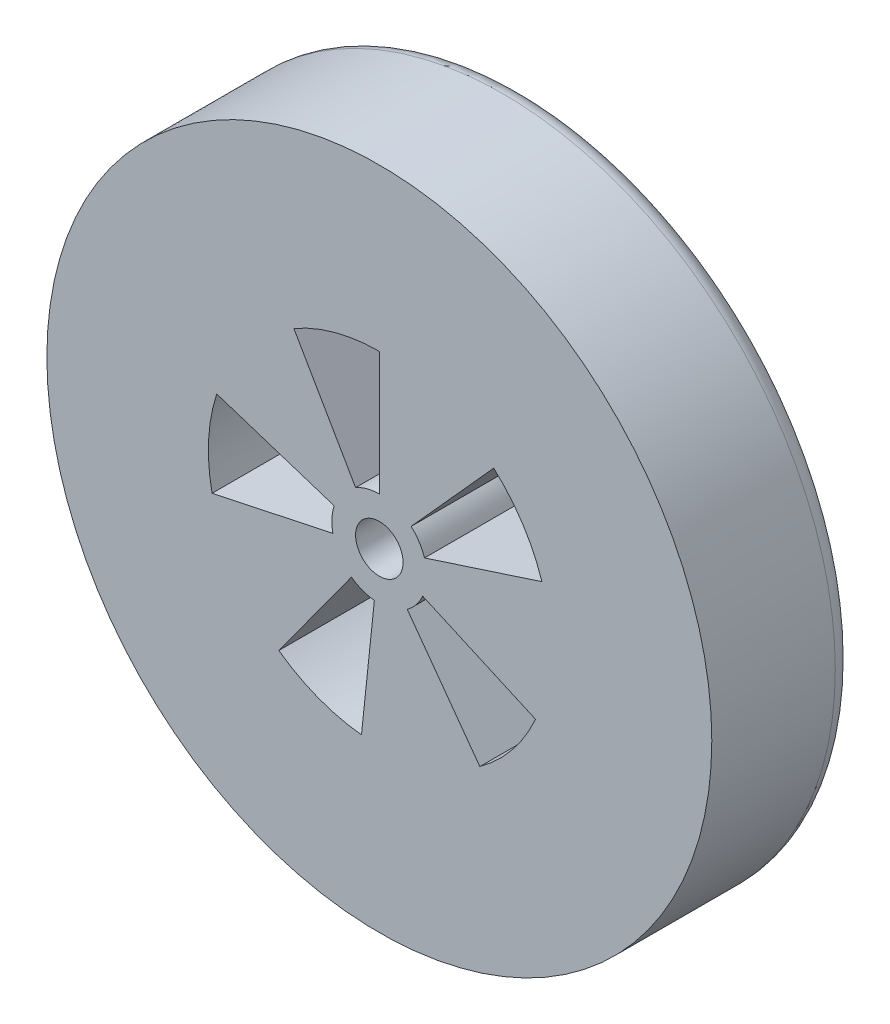
SolidWorks part; units mm, degrees
ref_plane "Front Plane" through (0, 0, 0) normal (0, 0, 1) x (1, 0, 0)
ref_plane "Top Plane" through (0, 0, 0) normal (0, 1, 0) x (1, 0, 0)
ref_plane "Right Plane" through (0, 0, 0) normal (1, 0, 0) x (0, 0, -1)
sketch "Sketch1" plane through (0, 0, 0) normal (0, 0, 1) x (1, 0, 0)
  circle A0 centre (0, 0) radius 35
  dimension "D1" = 70
extrude "Boss-Extrude1" add sketch "Sketch1" along normal blind 15
sketch "Sketch2" plane through (0, 0, 0) normal (0, 0, -1) x (-1, 0, 0)
  circle A0 centre (0, 0) radius 20
  dimension "D1" = 40
extrude "Cut-Extrude1" cut sketch "Sketch2" against normal blind 3
fillet "Fillet1" radius 2 1 edges at (35, 0, 0)
fillet "Fillet2" radius 2 1 edges at (-20, 0, 3)
sketch "Sketch4" plane through (0, 0, 3) normal (0, 0, -1) x (-1, 0, 0)
  circle A0 centre (0, 0) radius 2.5
  dimension "D1" = 5
extrude "Cut-Extrude2" cut sketch "Sketch4" against normal through all
sketch "Sketch5" plane through (0, 0, 3) normal (0, 0, -1) x (-1, 0, 0)
  line L0 (0, 5) -> (0, 18)
  line L1 (2.5, 4.3301) -> (9, 15.5885)
  line L2 (4.8907, -1.0396) -> (17.6067, -3.7424)
  line L3 (4.7553, 1.5451) -> (17.119, 5.5623)
  line L4 (0.5226, -4.9726) -> (1.8815, -17.9014)
  line L5 (2.9389, -4.0451) -> (10.5801, -14.5623)
  line L6 (-4.5677, -2.0337) -> (-16.4438, -7.3213)
  line L7 (-2.9389, -4.0451) -> (-10.5801, -14.5623)
  line L8 (-3.3457, 3.7157) -> (-12.0444, 13.3766)
  line L9 (-4.7553, 1.5451) -> (-17.119, 5.5623)
  circle A0 centre (0, 0) radius 5 construction
  circle A1 centre (0, 0) radius 18 construction
  circle A2 centre (0, 0) radius 18 construction
  arc A3 (0, 18) -> (9, 15.5885) centre (0, 0) cw
  arc A4 (0, 5) -> (2.5, 4.3301) centre (0, 0) cw
  arc A5 (17.119, 5.5623) -> (17.6067, -3.7424) centre (0, 0) cw
  arc A6 (4.7553, 1.5451) -> (4.8907, -1.0396) centre (0, 0) cw
  arc A7 (10.5801, -14.5623) -> (1.8815, -17.9014) centre (0, 0) cw
  arc A8 (2.9389, -4.0451) -> (0.5226, -4.9726) centre (0, 0) cw
  arc A9 (-10.5801, -14.5623) -> (-16.4438, -7.3213) centre (0, 0) cw
  arc A10 (-2.9389, -4.0451) -> (-4.5677, -2.0337) centre (0, 0) cw
  arc A11 (-17.119, 5.5623) -> (-12.0444, 13.3766) centre (0, 0) cw
  arc A12 (-4.7553, 1.5451) -> (-3.3457, 3.7157) centre (0, 0) cw
  point P34 (0, 0)
  dimension "D1" = 10
  dimension "D2" = 30
  dimension "D3" = 5
extrude "Cut-Extrude3" cut sketch "Sketch5" against normal through all
